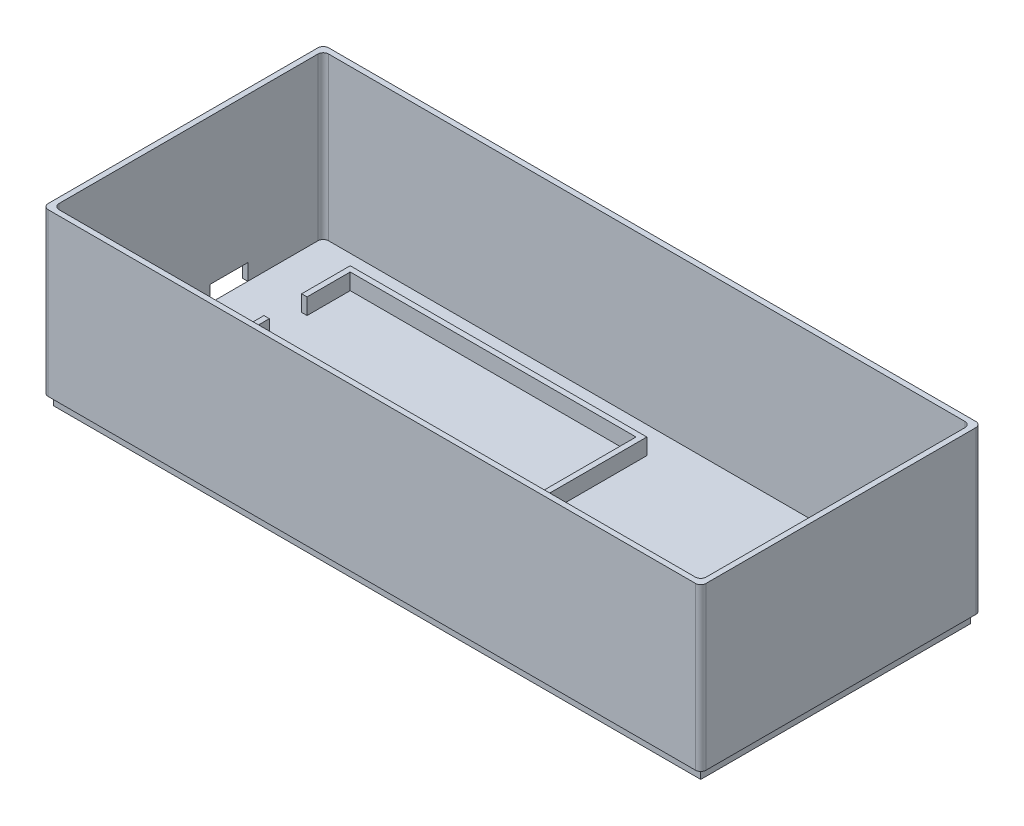
SolidWorks part; units mm, degrees
material "聚脂树脂"
ref_plane "前视基准面" through (0, 0, 0) normal (0, 0, 1) x (1, 0, 0)
ref_plane "上视基准面" through (0, 0, 0) normal (0, 1, 0) x (1, 0, 0)
ref_plane "右视基准面" through (0, 0, 0) normal (1, 0, 0) x (0, 0, -1)
other "Configuration Table"
sketch "草图1" plane through (0, 0, 0) normal (0, 1, 0) x (1, 0, 0)
  line L1 (0, 0) -> (120, 0)
  line L2 (0, 0) -> (0, -50)
  line L3 (0, -50) -> (120, -50)
  line L4 (120, 0) -> (120, -50)
  dimension "D1" = 120
  dimension "D2" = 50
extrude "凸台-拉伸1" add sketch "草图1" along normal blind 2
sketch "草图2" plane through (0, 2, 0) normal (0, 1, 0) x (1, 0, 0)
  line L0 (0, 0) -> (0, -50) construction
  line L1 (10, -5) -> (65, -5)
  line L2 (10, -5) -> (10, -30)
  line L3 (10, -30) -> (65, -30)
  line L4 (65, -5) -> (65, -30)
  line L5 (120, 0) -> (0, 0) construction
  dimension "D1" = 55
  dimension "D2" = 25
  dimension "D3" = 10
  dimension "D4" = 5
extrude "拉伸-薄壁1" add sketch "草图2" along normal blind 3 thin
sketch "草图3" plane through (0, 2, 0) normal (0, 1, 0) x (1, 0, 0)
  line L1 (10, -34) -> (33, -34)
  line L3 (10, -46) -> (33, -46)
  line L4 (0, 0) -> (0, -50)
  line L5 (0, -50) -> (120, -50)
  line L6 (120, -50) -> (120, 0)
  line L7 (120, 0) -> (0, 0)
  line L8 (0, 0) -> (0, -50)
  line L9 (0, -50) -> (120, -50)
  line L10 (120, -50) -> (120, 0)
  line L11 (120, 0) -> (0, 0)
  line L12 (0, 0) -> (0, -50)
  line L13 (120, 0) -> (0, 0)
  line L14 (120, -50) -> (120, 0)
  line L15 (0, -50) -> (120, -50)
  line L16 (0, 0) -> (0, -50)
  line L17 (120, 0) -> (0, 0)
  line L18 (120, -50) -> (120, 0)
  line L19 (0, -50) -> (120, -50)
  line L20 (33, -34) -> (33, -46)
  dimension "D3" = 12
  dimension "D4" = 23
  dimension "D5" = 4
  dimension "D6" = 33
  dimension "D1" = 0
  dimension "D2" = 0
extrude "拉伸-薄壁2" add sketch "草图3" along normal blind 3 thin contours L1 L20 L3
sketch "草图4" plane through (10, 0, 0) normal (-1, 0, 0) x (0, 0, 1)
  line L0 (17.5, 5) -> (17.5, -3.8018) construction
  line L1 (5, 5) -> (30, 5) construction
  line L2 (5, 2) -> (30, 2) construction
  line L3 (14, 5) -> (21, 5)
  line L4 (14, 5) -> (14, 2)
  line L5 (14, 2) -> (21, 2)
  line L6 (17.5, 5) -> (17.5, 2)
  line L7 (21, 5) -> (21, 2)
  dimension "D1" = 3
  dimension "D2" = 7
extrude "切除-拉伸1" cut sketch "草图4" against normal up to next contours L5 L7 L3 L4
sketch "草图5" plane through (0, 2, 0) normal (0, 1, 0) x (1, 0, 0)
  line L4 (0, 0) -> (0, -50)
  line L5 (0, -50) -> (120, -50)
  line L6 (120, -50) -> (120, 0)
  line L7 (120, 0) -> (0, 0)
  line L8 (0, 0) -> (0, -50)
  line L9 (0, -50) -> (120, -50)
  line L10 (120, -50) -> (120, 0)
  line L11 (120, 0) -> (0, 0)
  line L12 (0, 0) -> (0, -50)
  line L13 (120, 0) -> (0, 0)
  line L14 (120, -50) -> (120, 0)
  line L15 (0, -50) -> (120, -50)
  line L16 (0, 0) -> (0, -50)
  line L17 (120, 0) -> (0, 0)
  line L18 (120, -50) -> (120, 0)
  line L19 (0, -50) -> (120, -50)
  dimension "D1" = 0
  dimension "D2" = 0
extrude "拉伸-薄壁3" add sketch "草图5" along normal blind 30 separate body thin contours L11 L8 L9 L10
fillet "圆角1" radius 1 8 edges at (120, 17, 50) (121, 17, 51) (120, 17, 0) (121, 17, -1) (0, 17, 50) (-1, 17, 51) (-1, 17, -1) (0, 17, 0)
sketch "草图6" plane through (-1, 0, 0) normal (-1, 0, 0) x (0, 0, 1)
  line L0 (21, 5) -> (21, 2) construction
  line L1 (14, 5) -> (14, 2) construction
  line L2 (21, 5) -> (21, 2)
  line L3 (14, 5) -> (14, 2)
  line L4 (0, 2) -> (50, 2)
  line L5 (50, 2) -> (50, 32)
  line L6 (50, 32) -> (0, 32)
  line L7 (0, 32) -> (0, 2)
  line L8 (0, 2) -> (50, 2)
  line L9 (50, 2) -> (50, 32)
  line L10 (50, 32) -> (0, 32)
  line L11 (0, 32) -> (0, 2)
  line L12 (14, 5) -> (21, 5)
  line L13 (14, 2) -> (21, 2)
  line M5 (0, 2) -> (50, 2)
  dimension "D1" = 0
extrude "切除-拉伸2" cut sketch "草图6" against normal up to next (1 mm away) contours L12 L3 L2 M5
